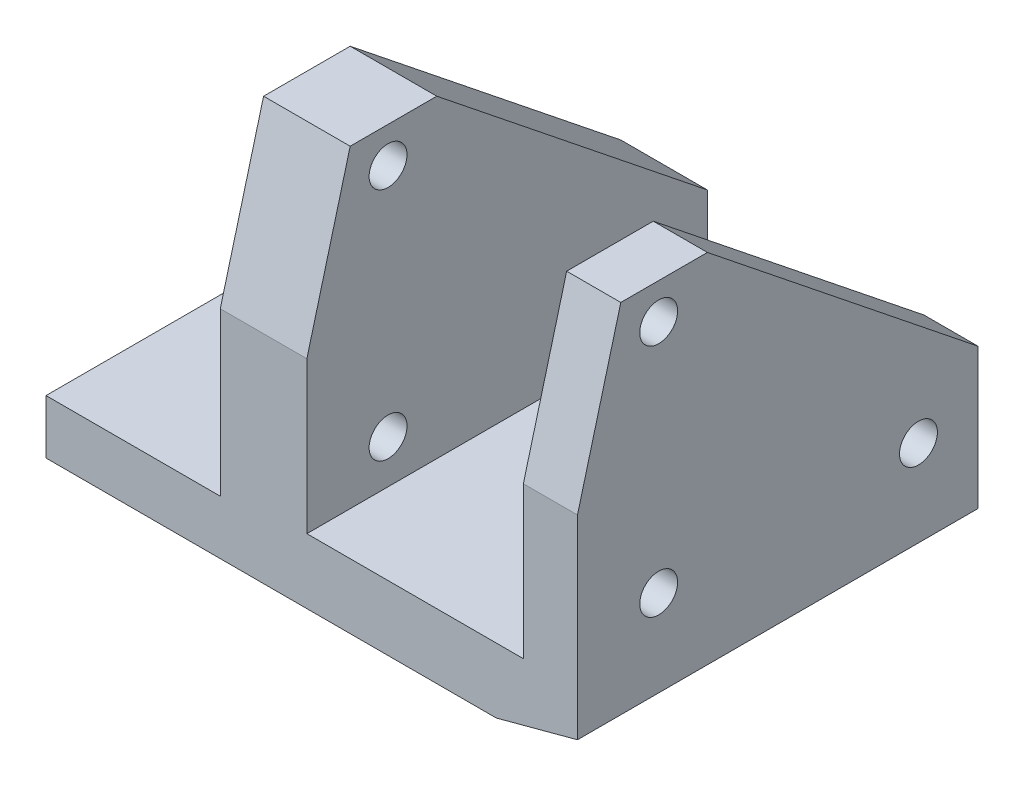
SolidWorks part; units mm, degrees
material "ABS"
ref_plane "Płaszczyzna przednia" through (0, 0, 0) normal (0, 0, 1) x (1, 0, 0)
ref_plane "Płaszczyzna górna" through (0, 0, 0) normal (0, 1, 0) x (1, 0, 0)
ref_plane "Płaszczyzna prawa" through (0, 0, 0) normal (1, 0, 0) x (0, 0, -1)
sketch "Szkic1" plane through (0, 0, 0) normal (0, 0, 1) x (1, 0, 0)
  line L1 (-12.8, -5) -> (12.8, -5)
  line L2 (-12.8, -5) -> (-12.8, 5)
  line L3 (-12.8, 5) -> (12.8, 5)
  line L4 (12.8, -5) -> (12.8, 5)
  line L5 (-12.8, -5) -> (12.8, 5) construction
  line L6 (-12.8, 5) -> (12.8, -5) construction
  point P0 (0, 0)
  dimension "D1" = 10
  dimension "D2" = 25.6
extrude "Dodanie-wyciągnięcie1" add sketch "Szkic1" along normal blind 5
sketch "Szkic2" plane through (0, 0, 5) normal (0, 0, 1) x (1, 0, 0)
  line L0 (0, 0) -> (0, -5) construction
  line L1 (-12.8, -5) -> (12.8, -5) construction
  circle A0 centre (-6, 0) radius 1.75
  circle A1 centre (6, 0) radius 1.75
  dimension "D1" = 3.5
  dimension "D2" = 12
extrude "Wytnij-wyciągnięcie1" cut sketch "Szkic2" against normal blind 5
sketch "Szkic3" plane through (0, 5, 0) normal (0, 1, 0) x (1, 0, 0)
  line L4 (12.8, 0) -> (-12.8, 0)
  line L5 (-12.8, 0) -> (-12.8, -5)
  line L6 (-12.8, -5) -> (12.8, -5)
  line L7 (12.8, -5) -> (12.8, 0)
  line L8 (12.8, 0) -> (-12.8, 0)
  line L9 (-12.8, 0) -> (-12.8, -5)
  line L10 (-12.8, -5) -> (12.8, -5)
  line L11 (12.8, -5) -> (12.8, 0)
  dimension "D1" = 0
extrude "Dodanie-wyciągnięcie2" add sketch "Szkic3" along normal blind 5
sketch "Szkic4" plane through (0, 0, 0) normal (0, 0, -1) x (-1, 0, 0)
  line L1 (-12.8, 10) -> (12.8, 10)
  line L2 (-12.8, 10) -> (-12.8, 5)
  line L3 (-12.8, 5) -> (12.8, 5)
  line L4 (12.8, 10) -> (12.8, 5)
  line L5 (12.8, 10) -> (12.8, -5) construction
  dimension "D1" = 5
  dimension "D2" = 25.6
extrude "Dodanie-wyciągnięcie3" add sketch "Szkic4" along normal blind 17
sketch "Szkic5" plane through (0, 10, 0) normal (0, 1, 0) x (1, 0, 0)
  line L0 (-12.8, -5) -> (12.8, -5) construction
  line L1 (-12.8, 17) -> (-12.8, -5) construction
  circle A0 centre (-0.8, 12) radius 1.75
  dimension "D1" = 3.5
  dimension "D2" = 17
  dimension "D3" = 12
extrude "Wytnij-wyciągnięcie2" cut sketch "Szkic5" against normal blind 20
sketch "Szkic6" plane through (0, 0, 5) normal (0, 0, 1) x (1, 0, 0)
  line L1 (12.8, 10) -> (10.8, 10)
  line L2 (12.8, 10) -> (12.8, -5)
  line L3 (12.8, -5) -> (10.8, -5)
  line L4 (10.8, 10) -> (10.8, -5)
  line L5 (-12.8, -5) -> (12.8, -5) construction
  dimension "D1" = 15
  dimension "D2" = 2
extrude "Wytnij-wyciągnięcie3" cut sketch "Szkic6" against normal through all
sketch "Szkic7" plane through (10.8, 0, 0) normal (1, 0, 0) x (0, 0, -1)
  line L0 (17, 10) -> (17, 20)
  line L1 (17, 20) -> (-8, 40)
  line L2 (-8, 40) -> (-16, 40)
  line L3 (-20, 5) -> (-5, 5)
  line L4 (-5, 10) -> (-5, -5) construction
  line L5 (-20, 5) -> (-20, 25)
  line L6 (-20, 25) -> (-16, 40)
  line L11 (0, -5) -> (0, 5)
  line L12 (0, 5) -> (17, 5)
  line L13 (17, 5) -> (17, 10)
  line L14 (17, 10) -> (-5, 10)
  line L15 (-5, 10) -> (-5, -5)
  line L16 (-5, -5) -> (0, -5)
  line L17 (0, -5) -> (0, 5)
  line L18 (0, 5) -> (17, 5)
  line L19 (17, 5) -> (17, 10)
  line L20 (17, 10) -> (-5, 10)
  line L21 (-5, 10) -> (-5, -5)
  line L22 (-5, -5) -> (0, -5)
  dimension "D1" = 0
  dimension "D2" = 10
  dimension "D3" = 15
  dimension "D4" = 30
  dimension "D5" = 5
  dimension "D6" = 8
  dimension "D7" = 20
  dimension "D8" = 4
extrude "Dodanie-wyciągnięcie4" add sketch "Szkic7" against normal blind 7.5 and the other way blind 0.5
sketch "Szkic8" plane through (3.3, 0, 0) normal (-1, 0, 0) x (0, 0, 1)
  line L0 (-17, 10) -> (-17, 20) construction
  line L1 (-17, 10) -> (5, 10) construction
  circle A0 centre (-11.5, 15) radius 1.75
  circle A1 centre (12.5, 15) radius 1.75
  circle A2 centre (12.5, 36.7) radius 1.75
  point P8 (0, 0)
  dimension "D1" = 5.5
  dimension "D3" = 3.5
  dimension "D4" = 24
  dimension "D5" = 21.7
  dimension "D2" = 5
extrude "Wytnij-wyciągnięcie4" cut sketch "Szkic8" against normal through all contours A1 | A2 | A0
sketch "Szkic9" plane through (10.8, 0, 0) normal (1, 0, 0) x (0, 0, -1)
  line L1 (-20, 5) -> (17, 5)
  line L2 (-20, 5) -> (-20, 11)
  line L3 (-20, 11) -> (17, 11)
  line L4 (17, 5) -> (17, 11)
  line L5 (17, 20) -> (17, 10) construction
  dimension "D1" = 6
  dimension "D2" = 37
extrude "Dodanie-wyciągnięcie5" add sketch "Szkic9" along normal blind 20.5
sketch "Szkic10" plane through (31.3, 0, 0) normal (1, 0, 0) x (0, 0, -1)
  line L4 (-20, 11) -> (-20, 5)
  line L5 (-20, 5) -> (17, 5)
  line L6 (0, 5) -> (-5, 5)
  line L7 (0, 5) -> (-5, 5)
  line L8 (-5, 5) -> (-5, -5)
  line L9 (-5, 5) -> (-5, -5)
  line L10 (-5, -5) -> (0, -5)
  line L11 (-5, -5) -> (0, -5)
  line L18 (17, 5) -> (17, 11)
  line L19 (17, 11) -> (-20, 11)
  line L20 (-20, 11) -> (-20, 5)
  line L21 (-20, 5) -> (17, 5)
  line L22 (17, 5) -> (17, 11)
  line L24 (0, -5) -> (0, 5)
  line L25 (0, -5) -> (0, 5)
  line L28 (-20, 25) -> (-20, 11)
  line L29 (-20, 11) -> (17, 11)
  line L30 (17, 11) -> (17, 20)
  line L31 (17, 20) -> (-8, 40)
  line L32 (-8, 40) -> (-16, 40)
  line L33 (-16, 40) -> (-20, 25)
  line L34 (-20, 25) -> (-20, 11)
  line L35 (-20, 11) -> (17, 11)
  line L36 (17, 11) -> (17, 20)
  line L37 (17, 20) -> (-8, 40)
  line L38 (-8, 40) -> (-16, 40)
  line L39 (-16, 40) -> (-20, 25)
  circle A0 centre (11.5, 15) radius 1.75 construction
  circle A1 centre (-12.5, 36.7) radius 1.75 construction
  circle A2 centre (-12.5, 15) radius 1.75 construction
  circle A3 centre (11.5, 15) radius 1.75
  circle A4 centre (-12.5, 36.7) radius 1.75
  circle A5 centre (-12.5, 15) radius 1.75
  line M11 (-20, 11) -> (-20, 5)
  line M12 (-20, 5) -> (17, 5)
  line M13 (17, 5) -> (17, 11)
  line M14 (17, 11) -> (-20, 11)
  dimension "D1" = 0
  dimension "D2" = 0
  dimension "D3" = 0
extrude "Dodanie-wyciągnięcie6" add sketch "Szkic10" along normal blind 5 contours M14 M11 M12 M13 | L38 L39 L34 L36 L37 A5 A4 A3 M14
sketch "Szkic11" plane through (0, 0, 5) normal (0, 0, 1) x (1, 0, 0)
  line L1 (3.3, 10) -> (-12.8, 10)
  line L2 (3.3, 10) -> (3.3, 5)
  line L3 (3.3, 5) -> (-12.8, 5)
  line L4 (-12.8, 10) -> (-12.8, 5)
  line L5 (-12.8, 10) -> (-12.8, -5) construction
  dimension "D1" = 5
  dimension "D2" = 16.1
extrude "Dodanie-wyciągnięcie7" add sketch "Szkic11" along normal up to surface (15 mm away) up to face at (20.55, 16.5, 20)
chamfer "Sfazowanie2" distance 7.5 angle 15 1 edges at (36.3, 5, 1.5)
